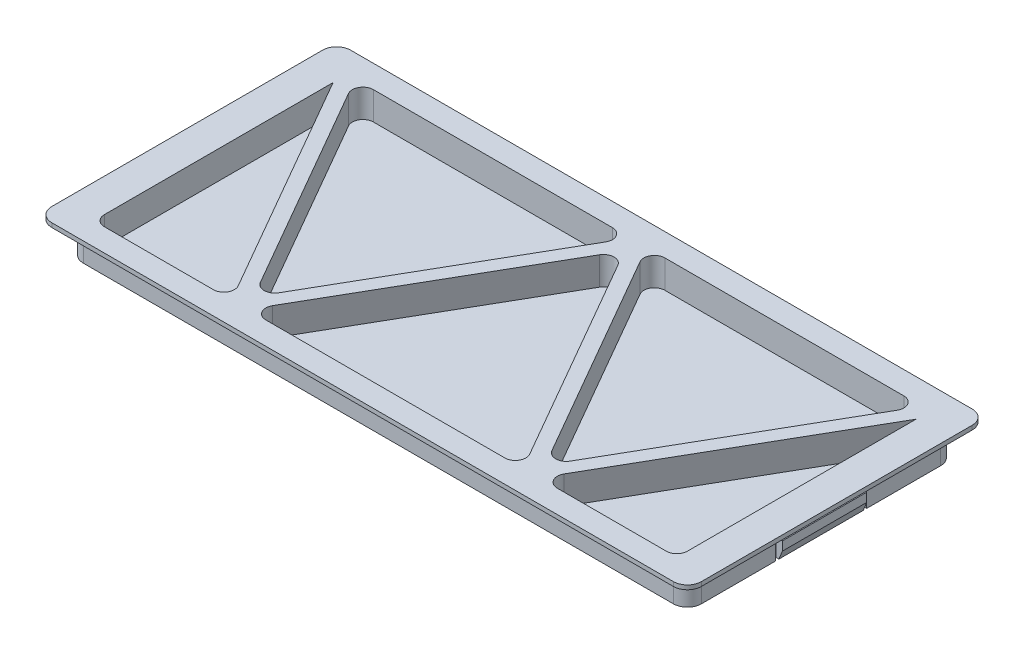
SolidWorks part; units mm, degrees
ref_plane "Front Plane" through (0, 0, 0) normal (0, 0, 1) x (1, 0, 0)
ref_plane "Top Plane" through (0, 0, 0) normal (0, 1, 0) x (1, 0, 0)
ref_plane "Right Plane" through (0, 0, 0) normal (1, 0, 0) x (0, 0, -1)
sketch "Sketch1" plane through (0, 0, 0) normal (0, 1, 0) x (1, 0, 0)
  line L1 (44.05, -19.05) -> (-44.05, -19.05)
  line L2 (44.05, -19.05) -> (44.05, 19.05)
  line L3 (44.05, 19.05) -> (-44.05, 19.05)
  line L4 (-44.05, -19.05) -> (-44.05, 19.05)
  line L5 (44.05, -19.05) -> (-44.05, 19.05) construction
  line L6 (44.05, 19.05) -> (-44.05, -19.05) construction
  point P0 (0, 0)
  dimension "D1" = 88.1
  dimension "D2" = 38.1
extrude "Boss-Extrude1" add sketch "Sketch1" along normal blind 5
shell "Shell1" thickness 1
sketch "Sketch2" plane through (0, 5, 0) normal (0, 1, 0) x (1, 0, 0)
  line L0 (-46.3, 21.3) -> (-46.3, -21.3)
  line L1 (-46.3, -21.3) -> (46.3, -21.3)
  line L2 (46.3, -21.3) -> (46.3, 21.3)
  line L3 (46.3, 21.3) -> (-46.3, 21.3)
  line L4 (-44.05, 19.05) -> (-44.05, -19.05)
  line L5 (-44.05, -19.05) -> (44.05, -19.05)
  line L6 (44.05, -19.05) -> (44.05, 19.05)
  line L7 (44.05, 19.05) -> (-44.05, 19.05)
  line L8 (-44.05, 19.05) -> (-44.05, -19.05)
  line L9 (-44.05, -19.05) -> (44.05, -19.05)
  line L10 (44.05, -19.05) -> (44.05, 19.05)
  line L11 (44.05, 19.05) -> (-44.05, 19.05)
  dimension "D1" = 0
  dimension "D2" = 2.25
extrude "Boss-Extrude2" add sketch "Sketch2" against normal blind 0.6
sketch "Sketch5" plane through (0, 0, 0) normal (0, -1, 0) x (1, 0, 0)
  line L0 (44.05, 19.05) -> (44.05, -19.05) construction
  line L1 (44.05, 19.05) -> (41.55, 19.05)
  line L2 (44.05, 19.05) -> (44.05, -19.05)
  line L3 (44.05, -19.05) -> (41.55, -19.05)
  line L4 (41.55, 19.05) -> (41.55, -19.05)
  line L5 (44.05, 6.5) -> (42.55, 6.5) construction
  line L6 (42.55, 6.5) -> (42.55, -6.5) construction
  line L7 (42.55, -6.5) -> (44.05, -6.5) construction
  point P6 (41.55, 0)
  point P12 (42.55, 0)
  dimension "D1" = 1
  dimension "D3" = 1.5
  dimension "D4" = 13
extrude "Boss-Extrude4" add sketch "Sketch5" against normal up to surface (5 mm away) up to face at (0, 5, 0)
sketch "Sketch7" plane through (0, 0, 0) normal (0, -1, 0) x (1, 0, 0)
  line L0 (41.55, 19.05) -> (41.55, -19.05) construction
  line L1 (42.05, 6.515) -> (44.05, 6.515)
  line L2 (42.05, 6.515) -> (42.05, -6.5)
  line L3 (42.05, -6.5) -> (44.05, -6.5)
  line L4 (44.05, 6.515) -> (44.05, -6.5)
  dimension "D1" = 0.5
extrude "Cut-Extrude2" cut sketch "Sketch7" against normal up to surface (4.4 mm away) up to face at (0, 4.4, 0)
sketch "Sketch8" plane through (0, 4.4, 0) normal (0, -1, 0) x (1, 0, 0)
  line L0 (44.05, -6.5) -> (44.05, -19.05) construction
  line L1 (44.05, 6.015) -> (43.65, 6.015)
  line L2 (44.05, 6.015) -> (44.05, -6.015)
  line L3 (44.05, -6.015) -> (43.65, -6.015)
  line L4 (43.65, 6.015) -> (43.65, -6.015)
  line L5 (44.05, 6.515) -> (42.05, 6.515) construction
  point P10 (43.65, 0)
  dimension "D1" = 0.4
  dimension "D2" = 0.5
extrude "Boss-Extrude5" add sketch "Sketch8" along normal up to surface (4.4 mm away) up to face at (21.525, 0, 0.0037)
sketch "Sketch9" plane through (0, 0, -6.015) normal (0, 0, -1) x (-1, 0, 0)
  line L0 (-46.3, 4.4) -> (46.3, 4.4) construction
  line L1 (-44.05, 0) -> (-44.55, 1.2375)
  line L2 (-44.05, 0) -> (-44.05, 2.5)
  line L3 (-44.05, 2.5) -> (-44.55, 2.5)
  line L4 (-44.55, 1.2375) -> (-44.55, 2.5)
  dimension "D1" = 0.5
  dimension "D2" = 1.9
  dimension "D3" = 22
extrude "Boss-Extrude6" add sketch "Sketch9" against normal up to surface (12.03 mm away) up to face at (43.85, 2.2, 6.015)
mirror "Mirror1" about plane through (0, 0, 0) normal (1, 0, 0) of "Boss-Extrude4", "Cut-Extrude2", "Boss-Extrude5", "Boss-Extrude6"
sketch "Sketch3" plane through (0, 5, 0) normal (0, 1, 0) x (1, 0, 0)
  line L0 (-41.55, 18.05) -> (-20.775, -18.05) construction
  line L1 (-41.55, -18.05) -> (41.55, -18.05) construction
  line L2 (-20.775, -18.05) -> (0, 18.05) construction
  line L3 (41.55, 18.05) -> (-41.55, 18.05) construction
  line L4 (0, 18.05) -> (20.775, -18.05) construction
  line L5 (20.775, -18.05) -> (41.55, 18.05) construction
  line L6 (-42.4167, 17.5512) -> (-20.775, -20.0549)
  line L7 (-20.775, -20.0549) -> (0, 16.0451)
  line L8 (0, 16.0451) -> (20.775, -20.0549)
  line L9 (20.775, -20.0549) -> (42.4167, 17.5512)
  line L10 (-40.6833, 18.5488) -> (-20.775, -16.0451)
  line L11 (-20.775, -16.0451) -> (0, 20.0549)
  line L12 (0, 20.0549) -> (20.775, -16.0451)
  line L13 (20.775, -16.0451) -> (40.6833, 18.5488)
  line L14 (-42.4167, 17.5512) -> (-40.6833, 18.5488)
  line L15 (42.4167, 17.5512) -> (40.6833, 18.5488)
  line L16 (-41.55, 18.05) -> (-20.775, -18.05) construction
  line L17 (20.775, -18.05) -> (41.55, 18.05) construction
  line L18 (41.55, 18.05) -> (-41.55, 18.05) construction
  line L19 (41.55, -18.05) -> (41.55, 18.05) construction
  line L20 (-41.55, 18.05) -> (-41.55, -18.05) construction
  line L21 (-41.55, -18.05) -> (-41.55, 18.05) construction
  dimension "D1" = 1
  dimension "D2" = 1
extrude "Boss-Extrude3" add sketch "Sketch3" against normal up to surface (4 mm away) up to face at (0, 1, 0)
sketch "Sketch4" plane through (0, 0, 0) normal (0, -1, 0) x (1, 0, 0)
  line L9 (-44.05, 19.05) -> (44.05, 19.05)
  line L10 (-44.05, 19.05) -> (-44.05, 119.05)
  line L11 (-44.05, 119.05) -> (44.05, 119.05)
  line L12 (44.05, 19.05) -> (44.05, 119.05)
  line L13 (44.05, -19.05) -> (-44.05, -19.05)
  line L14 (44.05, -19.05) -> (44.05, -119.05)
  line L15 (44.05, -119.05) -> (-44.05, -119.05)
  line L16 (-44.05, -19.05) -> (-44.05, -119.05)
  dimension "D1" = 100
  dimension "D2" = 100
extrude "Cut-Extrude1" cut sketch "Sketch4" against normal up to surface (4.4 mm away) up to face at (-43.85, 4.4, 0)
fillet "Fillet1" radius 2 8 edges at (-46.3, 4.7, 21.3) (-44.05, 2.2, 19.05) (-44.05, 2.2, -19.05) (44.05, 2.2, 19.05) (46.3, 4.7, 21.3) (44.05, 2.2, -19.05) (46.3, 4.7, -21.3) (-46.3, 4.7, -21.3)
fillet "Fillet2" radius 1.5 13 edges at (40.3962, 3, -18.05) (20.775, 3, 16.0451) (21.9288, 3, 18.05) (19.6212, 3, 18.05) (0, 3, -16.0451) (1.1538, 3, -18.05) (-1.1538, 3, -18.05) (-19.6212, 3, 18.05) (-21.9288, 3, 18.05) (-20.775, 3, 16.0451) (-40.3962, 3, -18.05) (41.55, 3, 18.05) (-41.55, 3, 18.05)
